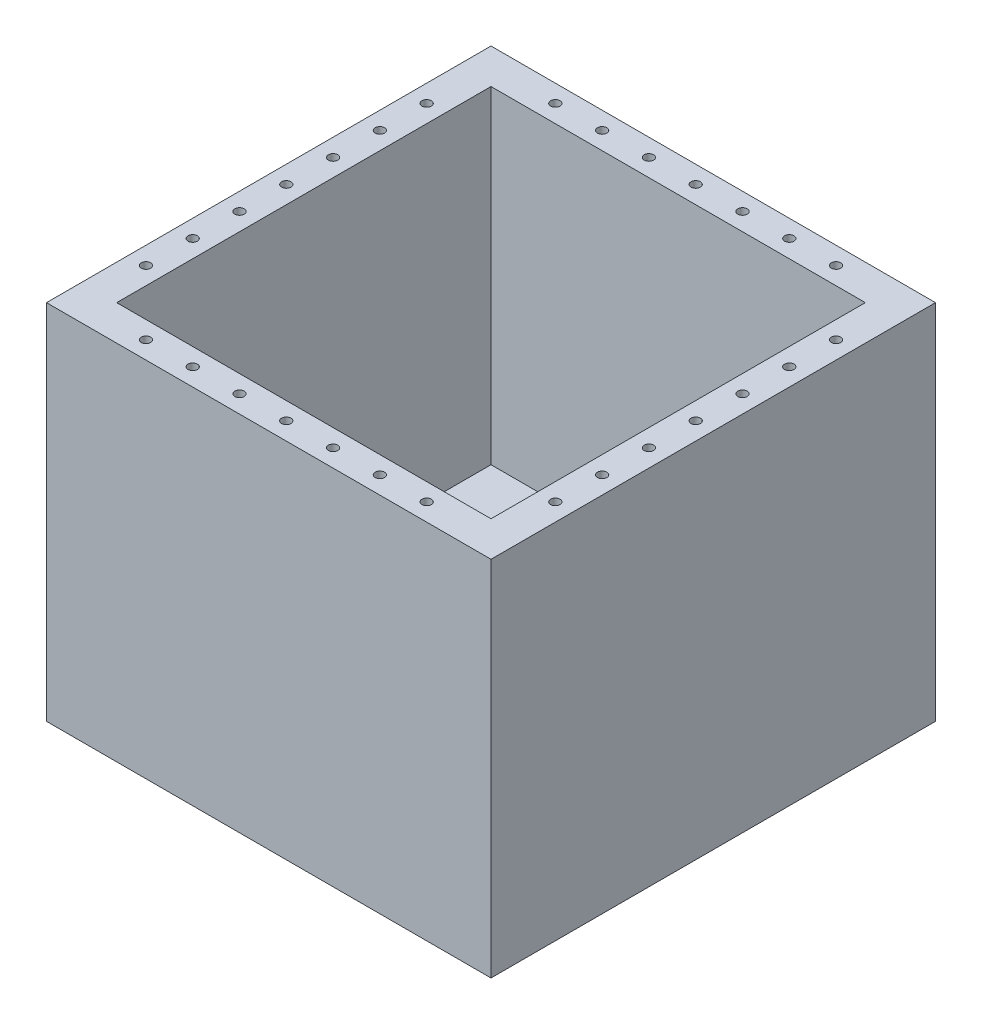
SolidWorks part; units mm, degrees
material "Glass"
ref_plane "Front Plane" through (0, 0, 0) normal (0, 0, 1) x (1, 0, 0)
ref_plane "Top Plane" through (0, 0, 0) normal (0, 1, 0) x (1, 0, 0)
ref_plane "Right Plane" through (0, 0, 0) normal (1, 0, 0) x (0, 0, -1)
sketch "Sketch1" plane through (0, 0, 0) normal (0, 1, 0) x (1, 0, 0)
  line L1 (-101.6, -101.6) -> (101.6, -101.6)
  line L2 (-101.6, -101.6) -> (-101.6, 101.6)
  line L3 (-101.6, 101.6) -> (101.6, 101.6)
  line L4 (101.6, -101.6) -> (101.6, 101.6)
  line L5 (-101.6, -101.6) -> (101.6, 101.6) construction
  line L6 (-101.6, 101.6) -> (101.6, -101.6) construction
  point P0 (0, 0)
  dimension "D1" = 203.2
  dimension "D2" = 203.2
extrude "Extrude-Thin1" add sketch "Sketch1" along normal blind 177.8 thin
sketch "Sketch2" plane through (0, 0, 0) normal (0, 1, 0) x (1, 0, 0)
  line L0 (120.65, 120.65) -> (-120.65, 120.65) construction
  line L1 (-120.65, -120.65) -> (120.65, -120.65)
  line L2 (-120.65, -120.65) -> (-120.65, 120.65)
  line L3 (-120.65, 120.65) -> (120.65, 120.65)
  line L4 (120.65, -120.65) -> (120.65, 120.65)
  line L5 (-120.65, -120.65) -> (120.65, 120.65) construction
  line L6 (-120.65, 120.65) -> (120.65, -120.65) construction
  line L7 (-120.65, 120.65) -> (-120.65, -120.65) construction
  point P0 (0, 0)
extrude "Boss-Extrude1" add sketch "Sketch2" against normal blind 19.05
hole_wizard "1/4-20 Tapped Hole1" positions "Sketch3" profile "Sketch4" tap size "1/4-20" standard "ANSI Inch"
sketch "Sketch3" plane through (0, 177.8, 0) normal (0, 1, 0) x (1, 0, 0)
  line L1 (0, 0) -> (0, 120.65) construction
  line L2 (120.65, 120.65) -> (-120.65, 120.65) construction
  line L3 (0, 0) -> (101.6, 0) construction
  line L4 (101.6, -101.6) -> (101.6, 101.6) construction
  point P10 (-111.125, 76.2)
  point P11 (-111.125, 50.8)
  point P12 (-111.125, 25.4)
  point P13 (-111.125, 0)
  point P14 (-111.125, -25.4)
  point P15 (-111.125, -50.8)
  point P16 (-111.125, -76.2)
  point P24 (111.125, -76.2)
  point P25 (111.125, -50.8)
  point P26 (111.125, -25.4)
  point P27 (111.125, 0)
  point P28 (111.125, 25.4)
  point P29 (111.125, 50.8)
  point P30 (111.125, 76.2)
  point P39 (-76.2, 111.125)
  point P40 (-50.8, 111.125)
  point P41 (-25.4, 111.125)
  point P42 (0, 111.125)
  point P43 (25.4, 111.125)
  point P44 (50.8, 111.125)
  point P45 (76.2, 111.125)
  point P54 (76.2, -111.125)
  point P55 (50.8, -111.125)
  point P56 (25.4, -111.125)
  point P57 (0, -111.125)
  point P58 (-25.4, -111.125)
  point P59 (-50.8, -111.125)
  point P60 (-76.2, -111.125)
sketch "Sketch4" plane through (-76.2, 177.8, 111.125) normal (1, 0, 0) x (0, 0, 1)
  line L0 (0, 0) -> (0, 18.0438)
  line L1 (0, 18.0438) -> (2.5527, 16.51)
  line L2 (2.5527, 16.51) -> (2.5527, 0)
  line L5 (2.5527, 0) -> (0, 0)
  line L10 (0, 18.0438) -> (-2.5527, 16.51) construction
  line L11 (0, -6.35) -> (0, 107.95) construction
  dimension "Tap Drill Dia." = 5.1054
  dimension "Tap Drill Depth" = 16.51
  dimension "Drill Angle" = 118
cosmetic thread "Hole Thread2" parameters "D1"=12.7, "D2"=6.35
cosmetic thread "Hole Thread3" parameters "D1"=12.7, "D2"=6.35
cosmetic thread "Hole Thread4" parameters "D1"=12.7, "D2"=6.35
cosmetic thread "Hole Thread5" parameters "D1"=12.7, "D2"=6.35
cosmetic thread "Hole Thread6" parameters "D1"=12.7, "D2"=6.35
cosmetic thread "Hole Thread7" parameters "D1"=12.7, "D2"=6.35
cosmetic thread "Hole Thread8" parameters "D1"=12.7, "D2"=6.35
cosmetic thread "Hole Thread11" parameters "D1"=12.7, "D2"=6.35
cosmetic thread "Hole Thread12" parameters "D1"=12.7, "D2"=6.35
cosmetic thread "Hole Thread13" parameters "D1"=12.7, "D2"=6.35
cosmetic thread "Hole Thread14" parameters "D1"=12.7, "D2"=6.35
cosmetic thread "Hole Thread15" parameters "D1"=12.7, "D2"=6.35
cosmetic thread "Hole Thread16" parameters "D1"=12.7, "D2"=6.35
cosmetic thread "Hole Thread17" parameters "D1"=12.7, "D2"=6.35
cosmetic thread "Hole Thread20" parameters "D1"=12.7, "D2"=6.35
cosmetic thread "Hole Thread21" parameters "D1"=12.7, "D2"=6.35
cosmetic thread "Hole Thread22" parameters "D1"=12.7, "D2"=6.35
cosmetic thread "Hole Thread23" parameters "D1"=12.7, "D2"=6.35
cosmetic thread "Hole Thread24" parameters "D1"=12.7, "D2"=6.35
cosmetic thread "Hole Thread25" parameters "D1"=12.7, "D2"=6.35
cosmetic thread "Hole Thread26" parameters "D1"=12.7, "D2"=6.35
cosmetic thread "Hole Thread29" parameters "D1"=12.7, "D2"=6.35
cosmetic thread "Hole Thread30" parameters "D1"=12.7, "D2"=6.35
cosmetic thread "Hole Thread31" parameters "D1"=12.7, "D2"=6.35
cosmetic thread "Hole Thread32" parameters "D1"=12.7, "D2"=6.35
cosmetic thread "Hole Thread33" parameters "D1"=12.7, "D2"=6.35
cosmetic thread "Hole Thread34" parameters "D1"=12.7, "D2"=6.35
cosmetic thread "Hole Thread35" parameters "D1"=12.7, "D2"=6.35
